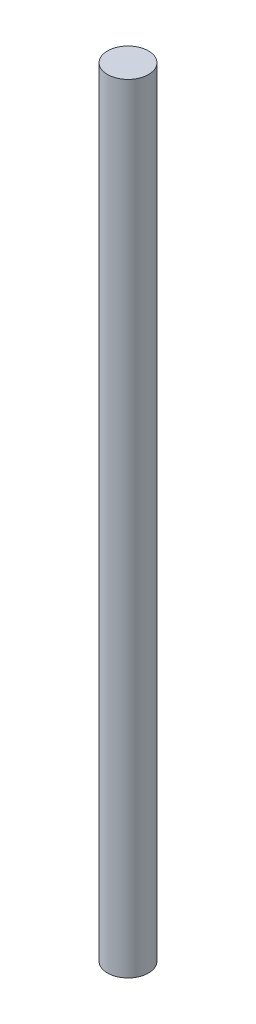
SolidWorks part; units mm, degrees
ref_plane "Front Plane" through (0, 0, 0) normal (0, 0, 1) x (1, 0, 0)
ref_plane "Top Plane" through (0, 0, 0) normal (0, 1, 0) x (1, 0, 0)
ref_plane "Right Plane" through (0, 0, 0) normal (1, 0, 0) x (0, 0, -1)
sketch "Sketch1" plane through (0, 0, 0) normal (0, 1, 0) x (1, 0, 0)
  circle A0 centre (0, 0) radius 3.175
  dimension "D1" = 6.35
extrude "Boss-Extrude1" add sketch "Sketch1" along normal blind 120.65
